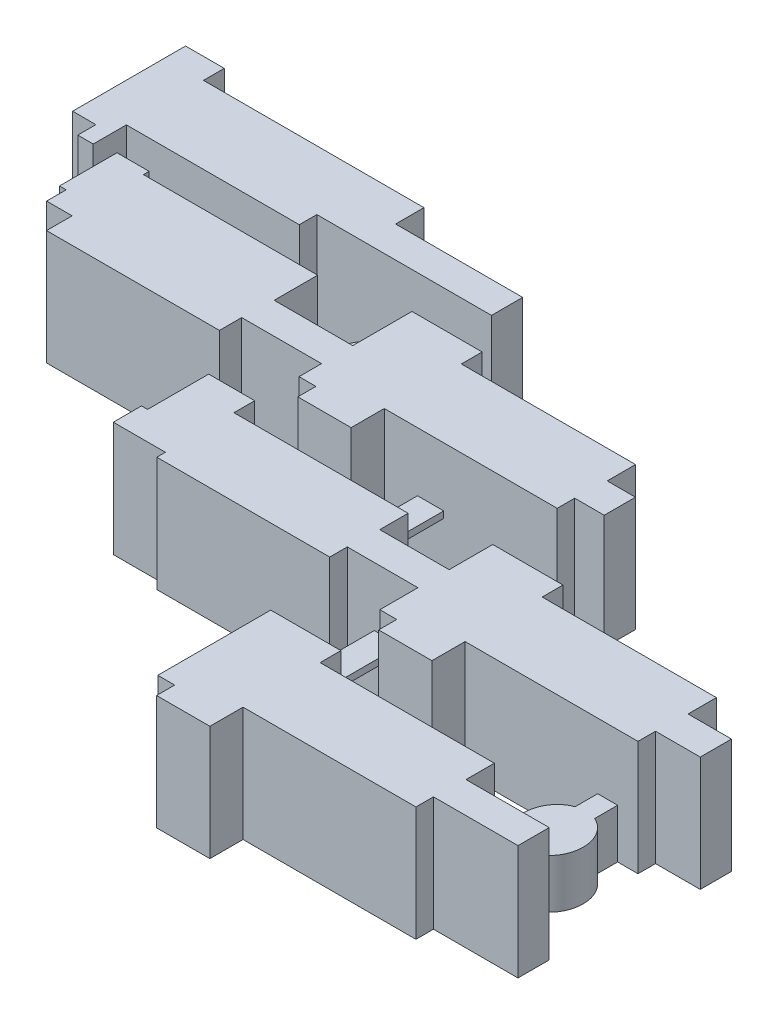
SolidWorks part; units mm, degrees
ref_plane "前视基准面" through (0, 0, 0) normal (0, 0, 1) x (1, 0, 0)
ref_plane "上视基准面" through (0, 0, 0) normal (0, 1, 0) x (1, 0, 0)
ref_plane "右视基准面" through (0, 0, 0) normal (1, 0, 0) x (0, 0, -1)
sketch "草图1" plane through (0, 0, 0) normal (0, 1, 0) x (1, 0, 0)
  line L0 (-50, 15) -> (-28.5714, 15)
  line L1 (-28.5714, 15) -> (-28.5714, 8.6508)
  line L2 (-28.5714, 8.6508) -> (24.6032, 8.6508)
  line L3 (24.6032, 8.6508) -> (24.6032, 0)
  line L4 (24.6032, 0) -> (50, 0)
  line L5 (50, 0) -> (50, -9.5238)
  line L6 (50, -9.5238) -> (24.2063, -9.5238)
  line L7 (24.2063, -9.5238) -> (24.2063, -14.881)
  line L8 (24.2063, -14.881) -> (-28.5714, -14.881)
  line L9 (-28.5714, -14.881) -> (-28.5714, -25)
  line L10 (-28.5714, -25) -> (-44.8413, -25)
  line L11 (-44.8413, -25) -> (-44.8413, -19.4749)
  line L12 (-44.8413, -19.4749) -> (-50, -19.4749)
  line L13 (-50, -19.4749) -> (-50, 15)
  line L14 (-107.7944, 61.5623) -> (-54.6198, 61.5623)
  line L15 (-55.0166, 38.0306) -> (-107.7944, 38.0306)
  line L16 (-121.8451, 67.9115) -> (-107.7944, 67.9115)
  line L17 (-123.6923, 40.6481) -> (-123.6923, 49.2584)
  line L18 (-107.7944, 40.6481) -> (-123.6923, 40.6481)
  line L19 (-33.4474, 43.3877) -> (-55.0166, 43.3877)
  line L20 (-54.6198, 52.9115) -> (-33.4474, 52.9115)
  line L21 (-123.6923, 49.2584) -> (-121.8451, 49.2584)
  line L22 (-107.7944, 67.9115) -> (-107.7944, 61.5623)
  line L23 (-55.0166, 43.3877) -> (-55.0166, 38.0306)
  line L25 (-121.8451, 49.2584) -> (-121.8451, 67.9115)
  line L26 (-54.6198, 61.5623) -> (-54.6198, 52.9115)
  line L27 (-107.7944, 38.0306) -> (-107.7944, 40.6481)
  line L28 (-12.0188, 59.882) -> (41.1558, 59.882)
  line L29 (40.7589, 36.3503) -> (-12.0188, 36.3503)
  line L30 (-33.4474, 66.2313) -> (-12.0188, 66.2313)
  line L31 (-28.2887, 26.2313) -> (-28.2887, 31.7564)
  line L32 (-12.0188, 26.2313) -> (-28.2887, 26.2313)
  line L33 (54.4107, 41.7074) -> (40.7589, 41.7074)
  line L34 (41.1558, 51.2313) -> (54.4107, 51.2313)
  line L35 (-28.2887, 31.7564) -> (-33.4474, 31.7564)
  line L36 (-12.0188, 66.2313) -> (-12.0188, 59.882)
  line L37 (40.7589, 41.7074) -> (40.7589, 36.3503)
  line L38 (54.4107, 51.2313) -> (54.4107, 41.7074)
  line L39 (-33.4474, 31.7564) -> (-33.4474, 43.3877)
  line L40 (41.1558, 59.882) -> (41.1558, 51.2313)
  line L41 (-12.0188, 36.3503) -> (-12.0188, 26.2313)
  line L42 (-184.54, 110.6917) -> (-131.3654, 110.6917)
  line L43 (-131.7622, 81.1094) -> (-184.54, 81.1094)
  line L44 (-194.3583, 112.4273) -> (-184.54, 112.4273)
  line L45 (-192.326, 88.9154) -> (-192.326, 94.8734)
  line L46 (-184.54, 88.9154) -> (-192.326, 88.9154)
  line L47 (-107.3925, 87.9035) -> (-131.7622, 87.9035)
  line L48 (-131.3654, 97.4273) -> (-107.3925, 97.4273)
  line L49 (-192.326, 94.8734) -> (-194.3583, 94.8734)
  line L50 (-184.54, 112.4273) -> (-184.54, 110.6917)
  line L51 (-131.7622, 87.9035) -> (-131.7622, 81.1094)
  line L53 (-194.3583, 94.8734) -> (-194.3583, 112.4273)
  line L54 (-131.3654, 110.6917) -> (-131.3654, 97.4273)
  line L55 (-184.54, 81.1094) -> (-184.54, 88.9154)
  line L56 (-85.9639, 109.1586) -> (-32.7893, 109.1586)
  line L57 (-33.1862, 85.6268) -> (-85.9639, 85.6268)
  line L58 (-107.3925, 115.5078) -> (-85.9639, 115.5078)
  line L59 (-102.2338, 75.5078) -> (-102.2338, 81.0329)
  line L60 (-85.9639, 75.5078) -> (-102.2338, 75.5078)
  line L61 (-24.1739, 90.984) -> (-33.1862, 90.984)
  line L62 (-32.7893, 100.5078) -> (-24.1739, 100.5078)
  line L63 (-102.2338, 81.0329) -> (-107.3925, 81.0329)
  line L64 (-85.9639, 115.5078) -> (-85.9639, 109.1586)
  line L65 (-33.1862, 90.984) -> (-33.1862, 85.6268)
  line L66 (-24.1739, 100.5078) -> (-24.1739, 90.984)
  line L67 (-107.3925, 81.0329) -> (-107.3925, 87.9035)
  line L68 (-32.7893, 109.1586) -> (-32.7893, 100.5078)
  line L69 (-85.9639, 85.6268) -> (-85.9639, 75.5078)
  line L70 (-200.2996, 144.7712) -> (-133.0007, 144.7712)
  line L71 (-147.5218, 121.2394) -> (-200.2996, 121.2394)
  line L72 (-212.1161, 151.1204) -> (-200.2996, 151.1204)
  line L73 (-205.0147, 111.1204) -> (-205.0147, 116.6455)
  line L74 (-200.2996, 111.1204) -> (-205.0147, 111.1204)
  line L75 (-94.2132, 126.5966) -> (-147.5218, 126.5966)
  line L76 (-133.0007, 136.1204) -> (-94.2132, 136.1204)
  line L77 (-205.0147, 116.6455) -> (-212.1161, 116.6455)
  line L78 (-200.2996, 151.1204) -> (-200.2996, 144.7712)
  line L79 (-147.5218, 126.5966) -> (-147.5218, 121.2394)
  line L80 (-94.2132, 136.1204) -> (-94.2132, 126.5966)
  line L81 (-212.1161, 116.6455) -> (-212.1161, 151.1204)
  line L82 (-133.0007, 144.7712) -> (-133.0007, 136.1204)
  line L83 (-200.2996, 121.2394) -> (-200.2996, 111.1204)
  line L84 (-107.3925, 97.4273) -> (-107.3925, 115.5078)
  line L85 (-33.4474, 52.9115) -> (-33.4474, 66.2313)
  point P17 (-196.1919, 85.8208)
  point P22 (-123.6923, 49.2584)
  dimension "D1" = 100
  dimension "D2" = 40
  dimension "D3" = 50
  dimension "D4" = 15
extrude "凸台-拉伸1" add sketch "草图1" along normal blind 35 contours L9 L10 L11 L12 L13 L0 L1 L2 L3 L4 L5 L6 L7 L8 | L20 L85 L30 L36 L28 L40 L34 L38 L33 L37 L29 L41 L32 L31 L35 L39 L19 L23 L15 L27 L18 L17 L21 L25 L16 L22 L14 L26 | L47 L51 L43 L55 L46 L45 L49 L53 L44 L50 L42 L54 L48 L84 L58 L64 L56 L68 L62 L66 L61 L65 L57 L69 L60 L59 L63 L67 | L70 L82 L76 L80 L75 L79 L71 L83 L74 L73 L77 L81 L72 L78
sketch "草图2" plane through (0, 0, 0) normal (0, 1, 0) x (1, 0, 0)
  line L0 (28.4439, 29.4877) -> (28.4439, 41.9998)
  line L1 (28.4439, 41.9998) -> (34.5392, 40.8869)
  line L2 (34.5392, 40.8869) -> (34.5392, 29.3173)
  line L3 (28.4439, 10.5167) -> (28.4439, 0.2047)
  line L4 (28.4439, 0.2047) -> (34.5392, 0.2047)
  line L5 (34.5392, 0.2047) -> (34.5392, 10.6872)
  line L6 (-48.0593, 77.4728) -> (-48.0593, 89.9849)
  line L7 (-48.0593, 48.1897) -> (-41.964, 48.1897)
  line L8 (-41.964, 88.872) -> (-41.964, 77.3023)
  line L9 (-41.964, 48.1897) -> (-41.964, 58.6722)
  line L10 (-48.0593, 89.9849) -> (-41.964, 88.872)
  line L11 (-48.0593, 58.5018) -> (-48.0593, 48.1897)
  line L12 (-123.0255, 135.3663) -> (-116.9302, 134.2534)
  line L13 (-123.0255, 93.5712) -> (-116.9302, 93.5712)
  line L14 (-116.9302, 93.5712) -> (-116.9302, 104.0537)
  line L15 (-116.9302, 134.2534) -> (-116.9302, 122.6838)
  line L16 (-123.0255, 122.8542) -> (-123.0255, 135.3663)
  line L17 (-123.0255, 103.8832) -> (-123.0255, 93.5712)
  ellipse E0 centre (31.2736, 20.0022) end of major axis (31.2736, 10.0205) minor radius 9.0878 (34.5392, 10.6872) -> (34.5392, 29.3173) ccw
  ellipse E1 centre (31.2736, 20.0022) end of major axis (31.2736, 10.0205) minor radius 9.0878 (28.4439, 29.4877) -> (28.4439, 10.5167) ccw
  ellipse E2 centre (-45.2296, 67.9873) end of major axis (-45.2296, 58.0055) minor radius 9.0878 (-48.0593, 77.4728) -> (-48.0593, 58.5018) ccw
  ellipse E3 centre (-45.2296, 67.9873) end of major axis (-45.2296, 58.0055) minor radius 9.0878 (-41.964, 58.6722) -> (-41.964, 77.3023) ccw
  ellipse E4 centre (-120.1958, 113.3687) end of major axis (-120.1958, 103.387) minor radius 9.0878 (-123.0255, 122.8542) -> (-123.0255, 103.8832) ccw
  ellipse E5 centre (-120.1958, 113.3687) end of major axis (-120.1958, 103.387) minor radius 9.0878 (-116.9302, 104.0537) -> (-116.9302, 122.6838) ccw
extrude "凸台-拉伸2" add sketch "草图2" along normal blind 15
sketch "草图3" plane through (0, 0, -121.2394) normal (0, 0, 1) x (1, 0, 0)
  line L1 (-167.977, 17) -> (-159.977, 17)
  line L2 (-167.977, 17) -> (-167.977, 15)
  line L3 (-167.977, 15) -> (-159.977, 15)
  line L4 (-159.977, 17) -> (-159.977, 15)
  line L5 (-147.5218, 0) -> (-200.2996, 0) construction
  dimension "D1" = 15
  dimension "D2" = 8
  dimension "D3" = 2
extrude "凸台-拉伸3" add sketch "草图3" along normal blind 23
sketch "草图4" plane through (0, 0, -87.9035) normal (0, 0, 1) x (1, 0, 0)
  line L1 (-75.8178, 17) -> (-67.8178, 17)
  line L2 (-75.8178, 17) -> (-75.8178, 15)
  line L3 (-75.8178, 15) -> (-67.8178, 15)
  line L4 (-67.8178, 17) -> (-67.8178, 15)
  line L5 (-48.0593, 0) -> (-85.9639, 0) construction
  dimension "D1" = 2
  dimension "D2" = 8
  dimension "D3" = 15
extrude "凸台-拉伸4" add sketch "草图4" along normal blind 30
sketch "草图5" plane through (0, 0, -43.3877) normal (0, 0, 1) x (1, 0, 0)
  line L1 (-46.7791, 17) -> (-38.7791, 17)
  line L2 (-46.7791, 17) -> (-46.7791, 15)
  line L3 (-46.7791, 15) -> (-38.7791, 15)
  line L4 (-38.7791, 17) -> (-38.7791, 15)
  line L5 (-33.4474, 0) -> (-55.0166, 0) construction
  dimension "D1" = 15
  dimension "D2" = 8
  dimension "D3" = 2
extrude "凸台-拉伸5" add sketch "草图5" along normal blind 33
